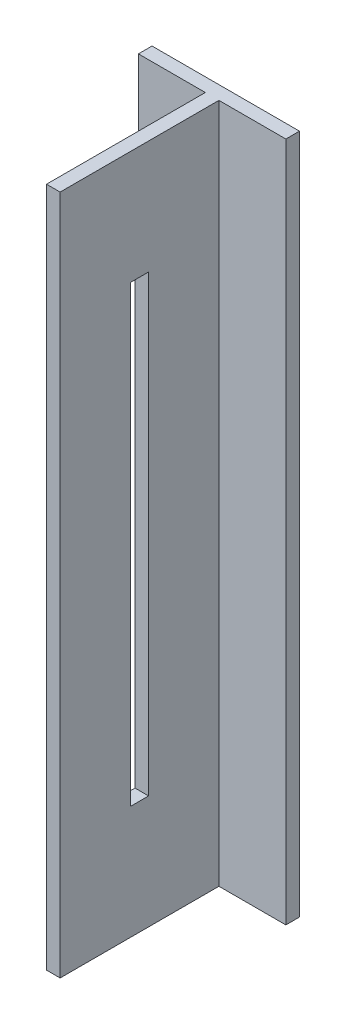
SolidWorks part; units mm, degrees
ref_plane "Front Plane" through (0, 0, 0) normal (0, 0, 1) x (1, 0, 0)
ref_plane "Top Plane" through (0, 0, 0) normal (0, 1, 0) x (1, 0, 0)
ref_plane "Right Plane" through (0, 0, 0) normal (1, 0, 0) x (0, 0, -1)
sketch "Sketch1" plane through (0, 0, 0) normal (0, 1, 0) x (1, 0, 0)
  line L0 (0, 0) -> (29.5, 0)
  line L1 (29.5, 0) -> (29.5, -70)
  line L2 (29.5, -70) -> (35.5, -70)
  line L3 (35.5, -70) -> (35.5, 0)
  line L4 (35.5, 0) -> (65, 0)
  line L5 (65, 0) -> (65, 6)
  line L6 (65, 6) -> (0, 6)
  line L7 (0, 6) -> (0, 0)
  dimension "D1" = 6
  dimension "D2" = 70
  dimension "D3" = 6
  dimension "D4" = 65
extrude "Boss-Extrude1" add sketch "Sketch1" along normal blind 300
sketch "Sketch2" plane through (35.5, 0, 0) normal (1, 0, 0) x (0, 0, -1)
  line L0 (-70, 150) -> (29.4353, 150) construction
  line L1 (-70, 300) -> (-70, 0) construction
  line L2 (-31, 250) -> (-31, 50)
  line L3 (-31, 50) -> (-39, 50)
  line L4 (-39, 50) -> (-39, 250)
  line L5 (-35, 50) -> (-35, 188.9219) construction
  line L6 (0, 300) -> (0, 0) construction
  line L7 (-31, 250) -> (-39, 250)
  point P13 (-39, 150)
  point P14 (-31, 150)
  dimension "D1" = 8
  dimension "D2" = 35
  dimension "D3" = 100
extrude "Cut-Extrude1" cut sketch "Sketch2" against normal through all
